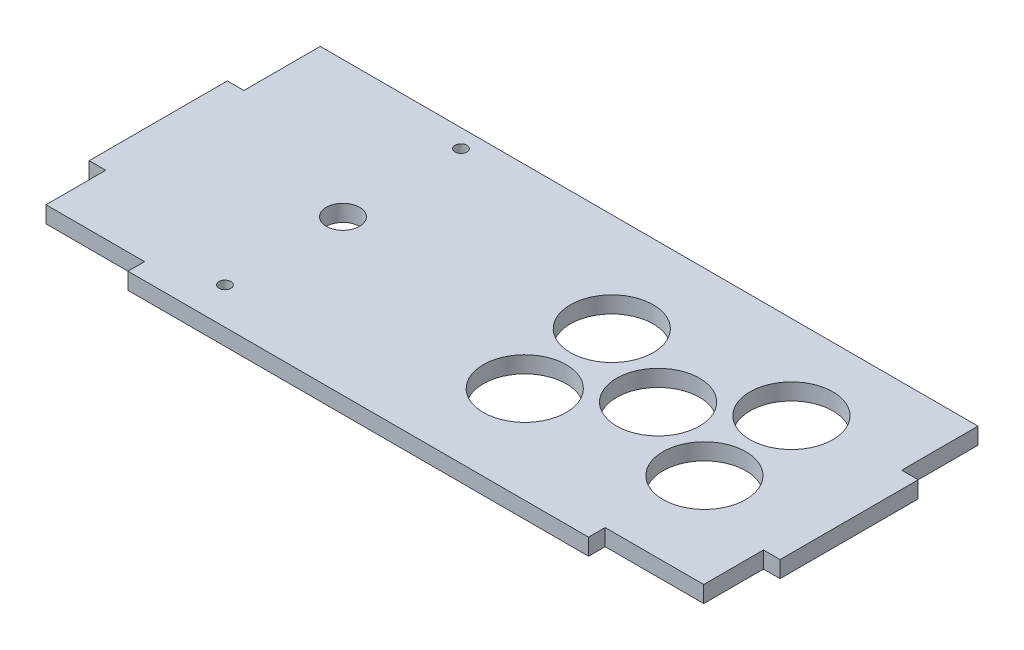
SolidWorks part; units mm, degrees
ref_plane "Front Plane" through (0, 0, 0) normal (0, 0, 1) x (1, 0, 0)
ref_plane "Top Plane" through (0, 0, 0) normal (0, 1, 0) x (1, 0, 0)
ref_plane "Right Plane" through (0, 0, 0) normal (1, 0, 0) x (0, 0, -1)
sketch "Sketch1" plane through (0, 0, 0) normal (0, 1, 0) x (1, 0, 0)
  line L1 (0, 0) -> (500, 0)
  line L2 (0, 0) -> (0, 210.49)
  line L3 (0, 210.49) -> (500, 210.49)
  line L4 (500, 0) -> (500, 210.49)
  dimension "D1" = 500
  dimension "D2" = 210.49
extrude "Boss-Extrude1" add sketch "Sketch1" along normal blind 12
sketch "Sketch2" plane through (0, 12, 0) normal (0, 1, 0) x (1, 0, 0)
  line L1 (500, 0) -> (416.6667, 0)
  line L2 (500, 0) -> (500, 12)
  line L3 (500, 12) -> (416.6667, 12)
  line L4 (416.6667, 0) -> (416.6667, 12)
  line L5 (500, 210.49) -> (488, 210.49)
  line L6 (500, 210.49) -> (500, 198.49)
  line L7 (500, 198.49) -> (488, 198.49)
  line L8 (488, 210.49) -> (488, 198.49)
  line L9 (0, 210.49) -> (12, 210.49)
  line L10 (0, 210.49) -> (0, 198.49)
  line L11 (0, 198.49) -> (12, 198.49)
  line L12 (12, 210.49) -> (12, 198.49)
  line L13 (0, 0) -> (83.3333, 0)
  line L14 (0, 0) -> (0, 12)
  line L15 (0, 12) -> (83.3333, 12)
  line L16 (83.3333, 0) -> (83.3333, 12)
  dimension "D2" = 12
  dimension "D3" = 12
  dimension "D4" = 12
  dimension "D5" = 83.3333
  dimension "D6" = 12
extrude "Cut-Extrude1" cut sketch "Sketch2" against normal through all
sketch "Sketch3" plane through (0, 12, 0) normal (0, 1, 0) x (1, 0, 0)
  line L1 (500, 12) -> (488, 12)
  line L2 (500, 12) -> (500, 55.245)
  line L3 (500, 55.245) -> (488, 55.245)
  line L4 (488, 12) -> (488, 55.245)
  line L5 (500, 198.49) -> (488, 198.49)
  line L6 (500, 198.49) -> (500, 155.245)
  line L7 (500, 155.245) -> (488, 155.245)
  line L8 (488, 198.49) -> (488, 155.245)
  line L9 (0, 198.49) -> (12, 198.49)
  line L10 (0, 198.49) -> (0, 155.245)
  line L11 (0, 155.245) -> (12, 155.245)
  line L12 (12, 198.49) -> (12, 155.245)
  line L13 (0, 12) -> (12, 12)
  line L14 (0, 12) -> (0, 55.245)
  line L15 (0, 55.245) -> (12, 55.245)
  line L16 (12, 12) -> (12, 55.245)
  dimension "D1" = 12
  dimension "D2" = 100
  dimension "D3" = 43.245
  dimension "D4" = 12
  dimension "D5" = 100
extrude "Cut-Extrude2" cut sketch "Sketch3" against normal through all
scale "Scale1" scale about centroid uniform scaling yes scale factor 0.5
hole_wizard "Ø12.0mm Dowel Slot1" positions "Sketch6" profile "Sketch7" size "Ø12.0" standard "ANSI Metric" slot yes end condition through all
sketch "Sketch6" plane through (0, 9, 0) normal (0, 1, 0) x (1, 0, 0)
  line L0 (125, 131.0871) -> (125, 81.0871) construction
  line L1 (369, 158.7096) -> (131, 158.7096) construction
  point P0 (188.5, 109.4096)
  dimension "D1" = 63.5
  dimension "D2" = 49.3
sketch "Sketch7" plane through (188.5, 9, -109.4096) normal (1, 0, 0) x (0, 0, 1)
  line L0 (0, 0) -> (0, 6)
  line L1 (0, 6) -> (6, 6)
  line L2 (6, 6) -> (6, 0)
  line L5 (6, 0) -> (0, 0)
  line L11 (0, -6.35) -> (0, 107.95) construction
  dimension "Thru Hole Dia." = 12
  dimension "Thru Hole Depth" = 6
hole_wizard "M4 Clearance Slot1" positions "Sketch8" profile "Sketch9" size "M4" standard "ANSI Metric" slot yes end condition through all
sketch "Sketch8" plane through (0, 3, 0) normal (0, -1, 0) x (-1, 0, 0)
  point P0 (-188.5, 152.1096)
  point P3 (-188.5, 66.7096)
sketch "Sketch9" plane through (188.5, 3, -152.1096) normal (1, 0, 0) x (0, 0, -1)
  line L0 (0, 0) -> (0, 6)
  line L1 (0, 6) -> (2.15, 6)
  line L2 (2.15, 6) -> (2.15, 0)
  line L5 (2.15, 0) -> (0, 0)
  line L11 (0, -6.35) -> (0, 107.95) construction
  dimension "Thru Hole Dia." = 4.3
  dimension "Thru Hole Depth" = 6
sketch "Sketch15" plane through (0, 9, 0) normal (0, 1, 0) x (1, 0, 0)
  line L0 (275.2283, 88.4803) -> (335, 93.7096) construction
  line L1 (335, 93.7096) -> (303.6046, 108.3495) construction
  line L2 (303.6046, 108.3495) -> (275.2283, 88.4803) construction
  line L5 (375, 81.0871) -> (375, 131.0871) construction
  line L7 (369, 158.7096) -> (131, 158.7096) construction
  line L8 (335, 93.7096) -> (330.6396, 143.5497) construction
  line L9 (330.6396, 143.5497) -> (270.8679, 138.3203) construction
  line L10 (270.8679, 138.3203) -> (275.2283, 88.4803) construction
  line L11 (303.6046, 108.3495) -> (331.9808, 128.2188) construction
  line L12 (303.6046, 108.3495) -> (272.2092, 122.9895) construction
  dimension "D1" = 30
  dimension "D2" = 60
  dimension "D3" = 65
  dimension "D4" = 40
hole_wizard "Ø1.0mm Dowel Slot1" positions "Sketch16" profile "Sketch17" size "Ø1.0" standard "ANSI Metric" slot yes end condition through all
sketch "Sketch16" plane through (0, 9, 0) normal (0, 1, 0) x (1, 0, 0)
  point P0 (275.2283, 88.4803)
  point P3 (335, 93.7096)
  point P6 (303.6046, 108.3495)
  point P9 (272.2092, 122.9895)
  point P12 (331.9808, 128.2188)
sketch "Sketch17" plane through (275.2283, 9, -88.4803) normal (1, 0, 0) x (0, 0, 1)
  line L0 (0, 0) -> (0, 6)
  line L1 (0, 6) -> (15, 6)
  line L2 (15, 6) -> (15, 0)
  line L5 (15, 0) -> (0, 0)
  line L11 (0, -6.35) -> (0, 107.95) construction
  dimension "Thru Hole Dia." = 30
  dimension "Thru Hole Depth" = 6
